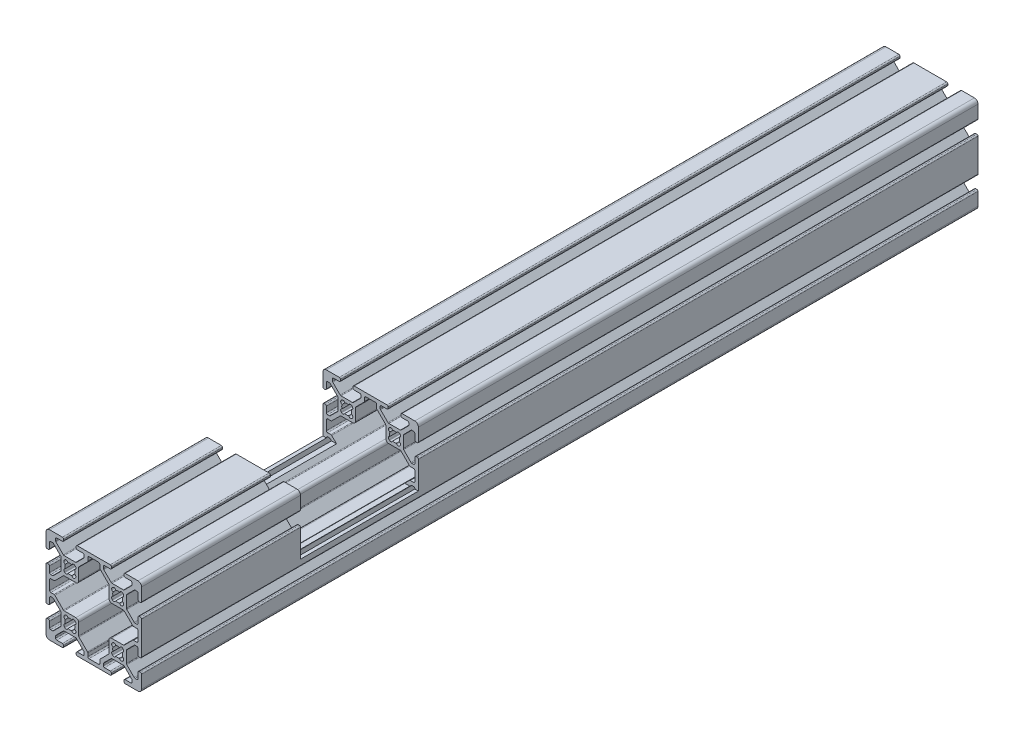
SolidWorks part; units mm, degrees
material "6105-T5 Aluminum"
ref_plane "Front Plane" through (0, 0, 0) normal (0, 0, 1) x (1, 0, 0)
ref_plane "Top Plane" through (0, 0, 0) normal (0, 1, 0) x (1, 0, 0)
ref_plane "Right Plane" through (0, 0, 0) normal (1, 0, 0) x (0, 0, -1)
sketch "Sketch1" plane through (0, 0, 0) normal (0, 0, 1) x (1, 0, 0)
  line L0 (-2.1249, 17.6955) -> (-2.3045, 17.8751)
  line L1 (-2.3045, 22.1249) -> (-2.1249, 22.3045)
  line L2 (2.1249, 22.3045) -> (2.3045, 22.1249)
  line L3 (2.3045, 17.8751) -> (2.1249, 17.6955)
  line L4 (-22.1249, 17.6955) -> (-22.3045, 17.8751)
  line L5 (-22.3045, 22.1249) -> (-22.1249, 22.3045)
  line L6 (-17.8751, 22.3045) -> (-17.6955, 22.1249)
  line L7 (-17.6955, 17.8751) -> (-17.8751, 17.6955)
  line L8 (-2.1249, -2.3045) -> (-2.3045, -2.1249)
  line L9 (-2.3045, 2.1249) -> (-2.1249, 2.3045)
  line L10 (2.1249, 2.3045) -> (2.3045, 2.1249)
  line L11 (2.3045, -2.1249) -> (2.1249, -2.3045)
  line L12 (-12.505, -7.992) -> (-12.505, -6.6448)
  line L13 (-12.6538, -6.2856) -> (-16.1962, -2.7431)
  line L14 (-16.345, -2.3839) -> (-16.345, 2.512)
  line L15 (-17.488, 3.655) -> (-22.3839, 3.655)
  line L16 (-22.7431, 3.8038) -> (-26.2856, 7.3462)
  line L17 (-26.6448, 7.495) -> (-27.992, 7.495)
  line L18 (-28.5, 8.003) -> (-28.5, 11.997)
  line L19 (-27.992, 12.505) -> (-26.6448, 12.505)
  line L20 (-26.2856, 12.6538) -> (-22.7431, 16.1962)
  line L21 (-22.3839, 16.345) -> (-17.488, 16.345)
  line L22 (-16.345, 17.488) -> (-16.345, 22.3839)
  line L23 (-16.1962, 22.7431) -> (-12.6538, 26.2856)
  line L24 (-12.505, 26.6448) -> (-12.505, 27.992)
  line L25 (-11.997, 28.5) -> (-8.003, 28.5)
  line L26 (-7.495, 27.992) -> (-7.495, 26.6448)
  line L27 (-7.3462, 26.2856) -> (-3.8038, 22.7431)
  line L28 (-3.655, 22.3839) -> (-3.655, 17.488)
  line L29 (-2.512, 16.345) -> (2.3839, 16.345)
  line L30 (2.7431, 16.1962) -> (6.2856, 12.6538)
  line L31 (6.6448, 12.505) -> (7.992, 12.505)
  line L32 (8.5, 11.997) -> (8.5, 8.003)
  line L33 (7.992, 7.495) -> (6.6448, 7.495)
  line L34 (6.2856, 7.3462) -> (2.7431, 3.8038)
  line L35 (2.3839, 3.655) -> (-2.512, 3.655)
  line L36 (-3.655, 2.512) -> (-3.655, -2.3839)
  line L37 (-3.8038, -2.7431) -> (-7.3462, -6.2856)
  line L38 (-7.495, -6.6448) -> (-7.495, -7.992)
  line L39 (-8.003, -8.5) -> (-11.997, -8.5)
  line L40 (-22.1249, -2.3045) -> (-22.3045, -2.1249)
  line L41 (-22.3045, 2.1249) -> (-22.1249, 2.3045)
  line L42 (-17.8751, 2.3045) -> (-17.6955, 2.1249)
  line L43 (-17.6955, -2.1249) -> (-17.8751, -2.3045)
  line L44 (-22.3839, -3.655) -> (-17.6161, -3.655)
  line L45 (-17.2569, -3.8038) -> (-14.1538, -6.9069)
  line L46 (-14.005, -7.2661) -> (-14.005, -7.992)
  line L47 (-14.513, -8.5) -> (-16.862, -8.5)
  line L48 (-17.37, -9.008) -> (-17.37, -9.492)
  line L49 (-16.862, -10) -> (-3.138, -10)
  line L50 (-2.63, -9.492) -> (-2.63, -9.008)
  line L51 (-3.138, -8.5) -> (-5.487, -8.5)
  line L52 (-5.995, -7.992) -> (-5.995, -7.2661)
  line L53 (-5.8462, -6.9069) -> (-2.7431, -3.8038)
  line L54 (-2.3839, -3.655) -> (2.3839, -3.655)
  line L55 (2.7431, -3.8038) -> (5.8462, -6.9069)
  line L56 (5.995, -7.2661) -> (5.995, -7.992)
  line L57 (5.487, -8.5) -> (3.138, -8.5)
  line L58 (2.63, -9.008) -> (2.63, -9.492)
  line L59 (3.138, -10) -> (8.5, -10)
  line L60 (10, -8.5) -> (10, -3.138)
  line L61 (9.492, -2.63) -> (9.008, -2.63)
  line L62 (8.5, -3.138) -> (8.5, -5.487)
  line L63 (7.992, -5.995) -> (7.2661, -5.995)
  line L64 (6.9069, -5.8462) -> (3.8038, -2.7431)
  line L65 (3.655, -2.3839) -> (3.655, 2.3839)
  line L66 (3.8038, 2.7431) -> (6.9069, 5.8462)
  line L67 (7.2661, 5.995) -> (7.992, 5.995)
  line L68 (8.5, 5.487) -> (8.5, 3.138)
  line L69 (9.008, 2.63) -> (9.492, 2.63)
  line L70 (10, 3.138) -> (10, 16.862)
  line L71 (9.492, 17.37) -> (9.008, 17.37)
  line L72 (8.5, 16.862) -> (8.5, 14.513)
  line L73 (7.992, 14.005) -> (7.2661, 14.005)
  line L74 (6.9069, 14.1538) -> (3.8038, 17.2569)
  line L75 (3.655, 17.6161) -> (3.655, 22.3839)
  line L76 (3.8038, 22.7431) -> (6.9069, 25.8462)
  line L77 (7.2661, 25.995) -> (7.992, 25.995)
  line L78 (8.5, 25.487) -> (8.5, 23.138)
  line L79 (9.008, 22.63) -> (9.492, 22.63)
  line L80 (10, 23.138) -> (10, 28.5)
  line L81 (8.5, 30) -> (3.138, 30)
  line L82 (2.63, 29.492) -> (2.63, 29.008)
  line L83 (3.138, 28.5) -> (5.487, 28.5)
  line L84 (5.995, 27.992) -> (5.995, 27.2661)
  line L85 (5.8462, 26.9069) -> (2.7431, 23.8038)
  line L86 (2.3839, 23.655) -> (-2.3839, 23.655)
  line L87 (-2.7431, 23.8038) -> (-5.8462, 26.9069)
  line L88 (-5.995, 27.2661) -> (-5.995, 27.992)
  line L89 (-5.487, 28.5) -> (-3.138, 28.5)
  line L90 (-2.63, 29.008) -> (-2.63, 29.492)
  line L91 (-3.138, 30) -> (-16.862, 30)
  line L92 (-17.37, 29.492) -> (-17.37, 29.008)
  line L93 (-16.862, 28.5) -> (-14.513, 28.5)
  line L94 (-14.005, 27.992) -> (-14.005, 27.2661)
  line L95 (-14.1538, 26.9069) -> (-17.2569, 23.8038)
  line L96 (-17.6161, 23.655) -> (-22.3839, 23.655)
  line L97 (-22.7431, 23.8038) -> (-25.8462, 26.9069)
  line L98 (-25.995, 27.2661) -> (-25.995, 27.992)
  line L99 (-25.487, 28.5) -> (-23.138, 28.5)
  line L100 (-22.63, 29.008) -> (-22.63, 29.492)
  line L101 (-23.138, 30) -> (-28.5, 30)
  line L102 (-30, 28.5) -> (-30, 23.138)
  line L103 (-29.492, 22.63) -> (-29.008, 22.63)
  line L104 (-28.5, 23.138) -> (-28.5, 25.487)
  line L105 (-27.992, 25.995) -> (-27.2661, 25.995)
  line L106 (-26.9069, 25.8462) -> (-23.8038, 22.7431)
  line L107 (-23.655, 22.3839) -> (-23.655, 17.6161)
  line L108 (-23.8038, 17.2569) -> (-26.9069, 14.1538)
  line L109 (-27.2661, 14.005) -> (-27.992, 14.005)
  line L110 (-28.5, 14.513) -> (-28.5, 16.862)
  line L111 (-29.008, 17.37) -> (-29.492, 17.37)
  line L112 (-30, 16.862) -> (-30, 3.138)
  line L113 (-29.492, 2.63) -> (-29.008, 2.63)
  line L114 (-28.5, 3.138) -> (-28.5, 5.487)
  line L115 (-27.992, 5.995) -> (-27.2661, 5.995)
  line L116 (-26.9069, 5.8462) -> (-23.8038, 2.7431)
  line L117 (-23.655, 2.3839) -> (-23.655, -2.3839)
  line L118 (-23.8038, -2.7431) -> (-26.9069, -5.8462)
  line L119 (-27.2661, -5.995) -> (-27.992, -5.995)
  line L120 (-28.5, -5.487) -> (-28.5, -3.138)
  line L121 (-29.008, -2.63) -> (-29.492, -2.63)
  line L122 (-30, -3.138) -> (-30, -8.5)
  line L123 (-28.5, -10) -> (-23.138, -10)
  line L124 (-22.63, -9.492) -> (-22.63, -9.008)
  line L125 (-23.138, -8.5) -> (-25.487, -8.5)
  line L126 (-25.995, -7.992) -> (-25.995, -7.2661)
  line L127 (-25.8462, -6.9069) -> (-22.7431, -3.8038)
  arc A0 (-1.9351, 19.196) -> (-2.3045, 17.8751) centre (-1.748, 18.4316) ccw
  arc A1 (-1.9351, 20.804) -> (-1.9351, 19.196) centre (0, 20) ccw
  arc A2 (-2.3045, 22.1249) -> (-1.9351, 20.804) centre (-1.748, 21.5684) ccw
  arc A3 (-0.804, 21.9351) -> (-2.1249, 22.3045) centre (-1.5684, 21.748) ccw
  arc A4 (0.804, 21.9351) -> (-0.804, 21.9351) centre (0, 20) ccw
  arc A5 (2.1249, 22.3045) -> (0.804, 21.9351) centre (1.5684, 21.748) ccw
  arc A6 (1.9351, 20.804) -> (2.3045, 22.1249) centre (1.748, 21.5684) ccw
  arc A7 (1.9351, 19.196) -> (1.9351, 20.804) centre (0, 20) ccw
  arc A8 (2.3045, 17.8751) -> (1.9351, 19.196) centre (1.748, 18.4316) ccw
  arc A9 (0.804, 18.0649) -> (2.1249, 17.6955) centre (1.5684, 18.252) ccw
  arc A10 (-0.804, 18.0649) -> (0.804, 18.0649) centre (0, 20) ccw
  arc A11 (-2.1249, 17.6955) -> (-0.804, 18.0649) centre (-1.5684, 18.252) ccw
  arc A12 (-21.9351, 19.196) -> (-22.3045, 17.8751) centre (-21.748, 18.4316) ccw
  arc A13 (-21.9351, 20.804) -> (-21.9351, 19.196) centre (-20, 20) ccw
  arc A14 (-22.3045, 22.1249) -> (-21.9351, 20.804) centre (-21.748, 21.5684) ccw
  arc A15 (-20.804, 21.9351) -> (-22.1249, 22.3045) centre (-21.5684, 21.748) ccw
  arc A16 (-19.196, 21.9351) -> (-20.804, 21.9351) centre (-20, 20) ccw
  arc A17 (-17.8751, 22.3045) -> (-19.196, 21.9351) centre (-18.4316, 21.748) ccw
  arc A18 (-18.0649, 20.804) -> (-17.6955, 22.1249) centre (-18.252, 21.5684) ccw
  arc A19 (-18.0649, 19.196) -> (-18.0649, 20.804) centre (-20, 20) ccw
  arc A20 (-17.6955, 17.8751) -> (-18.0649, 19.196) centre (-18.252, 18.4316) ccw
  arc A21 (-19.196, 18.0649) -> (-17.8751, 17.6955) centre (-18.4316, 18.252) ccw
  arc A22 (-20.804, 18.0649) -> (-19.196, 18.0649) centre (-20, 20) ccw
  arc A23 (-22.1249, 17.6955) -> (-20.804, 18.0649) centre (-21.5684, 18.252) ccw
  arc A24 (-1.9351, -0.804) -> (-2.3045, -2.1249) centre (-1.748, -1.5684) ccw
  arc A25 (-1.9351, 0.804) -> (-1.9351, -0.804) centre (0, 0) ccw
  arc A26 (-2.3045, 2.1249) -> (-1.9351, 0.804) centre (-1.748, 1.5684) ccw
  arc A27 (-0.804, 1.9351) -> (-2.1249, 2.3045) centre (-1.5684, 1.748) ccw
  arc A28 (0.804, 1.9351) -> (-0.804, 1.9351) centre (0, 0) ccw
  arc A29 (2.1249, 2.3045) -> (0.804, 1.9351) centre (1.5684, 1.748) ccw
  arc A30 (1.9351, 0.804) -> (2.3045, 2.1249) centre (1.748, 1.5684) ccw
  arc A31 (1.9351, -0.804) -> (1.9351, 0.804) centre (0, 0) ccw
  arc A32 (2.3045, -2.1249) -> (1.9351, -0.804) centre (1.748, -1.5684) ccw
  arc A33 (0.804, -1.9351) -> (2.1249, -2.3045) centre (1.5684, -1.748) ccw
  arc A34 (-0.804, -1.9351) -> (0.804, -1.9351) centre (0, 0) ccw
  arc A35 (-2.1249, -2.3045) -> (-0.804, -1.9351) centre (-1.5684, -1.748) ccw
  arc A36 (-12.505, -7.992) -> (-11.997, -8.5) centre (-11.997, -7.992) ccw
  arc A37 (-12.505, -6.6448) -> (-12.6538, -6.2856) centre (-13.013, -6.6448) ccw
  arc A38 (-16.345, -2.3839) -> (-16.1962, -2.7431) centre (-15.837, -2.3839) ccw
  arc A39 (-16.345, 2.512) -> (-17.488, 3.655) centre (-17.488, 2.512) ccw
  arc A40 (-22.7431, 3.8038) -> (-22.3839, 3.655) centre (-22.3839, 4.163) ccw
  arc A41 (-26.2856, 7.3462) -> (-26.6448, 7.495) centre (-26.6448, 6.987) ccw
  arc A42 (-28.5, 8.003) -> (-27.992, 7.495) centre (-27.992, 8.003) ccw
  arc A43 (-27.992, 12.505) -> (-28.5, 11.997) centre (-27.992, 11.997) ccw
  arc A44 (-26.6448, 12.505) -> (-26.2856, 12.6538) centre (-26.6448, 13.013) ccw
  arc A45 (-22.3839, 16.345) -> (-22.7431, 16.1962) centre (-22.3839, 15.837) ccw
  arc A46 (-17.488, 16.345) -> (-16.345, 17.488) centre (-17.488, 17.488) ccw
  arc A47 (-16.1962, 22.7431) -> (-16.345, 22.3839) centre (-15.837, 22.3839) ccw
  arc A48 (-12.6538, 26.2856) -> (-12.505, 26.6448) centre (-13.013, 26.6448) ccw
  arc A49 (-11.997, 28.5) -> (-12.505, 27.992) centre (-11.997, 27.992) ccw
  arc A50 (-7.495, 27.992) -> (-8.003, 28.5) centre (-8.003, 27.992) ccw
  arc A51 (-7.495, 26.6448) -> (-7.3462, 26.2856) centre (-6.987, 26.6448) ccw
  arc A52 (-3.655, 22.3839) -> (-3.8038, 22.7431) centre (-4.163, 22.3839) ccw
  arc A53 (-3.655, 17.488) -> (-2.512, 16.345) centre (-2.512, 17.488) ccw
  arc A54 (2.7431, 16.1962) -> (2.3839, 16.345) centre (2.3839, 15.837) ccw
  arc A55 (6.2856, 12.6538) -> (6.6448, 12.505) centre (6.6448, 13.013) ccw
  arc A56 (8.5, 11.997) -> (7.992, 12.505) centre (7.992, 11.997) ccw
  arc A57 (7.992, 7.495) -> (8.5, 8.003) centre (7.992, 8.003) ccw
  arc A58 (6.6448, 7.495) -> (6.2856, 7.3462) centre (6.6448, 6.987) ccw
  arc A59 (2.3839, 3.655) -> (2.7431, 3.8038) centre (2.3839, 4.163) ccw
  arc A60 (-2.512, 3.655) -> (-3.655, 2.512) centre (-2.512, 2.512) ccw
  arc A61 (-3.8038, -2.7431) -> (-3.655, -2.3839) centre (-4.163, -2.3839) ccw
  arc A62 (-7.3462, -6.2856) -> (-7.495, -6.6448) centre (-6.987, -6.6448) ccw
  arc A63 (-8.003, -8.5) -> (-7.495, -7.992) centre (-8.003, -7.992) ccw
  arc A64 (-21.9351, -0.804) -> (-22.3045, -2.1249) centre (-21.748, -1.5684) ccw
  arc A65 (-21.9351, 0.804) -> (-21.9351, -0.804) centre (-20, 0) ccw
  arc A66 (-22.3045, 2.1249) -> (-21.9351, 0.804) centre (-21.748, 1.5684) ccw
  arc A67 (-20.804, 1.9351) -> (-22.1249, 2.3045) centre (-21.5684, 1.748) ccw
  arc A68 (-19.196, 1.9351) -> (-20.804, 1.9351) centre (-20, 0) ccw
  arc A69 (-17.8751, 2.3045) -> (-19.196, 1.9351) centre (-18.4316, 1.748) ccw
  arc A70 (-18.0649, 0.804) -> (-17.6955, 2.1249) centre (-18.252, 1.5684) ccw
  arc A71 (-18.0649, -0.804) -> (-18.0649, 0.804) centre (-20, 0) ccw
  arc A72 (-17.6955, -2.1249) -> (-18.0649, -0.804) centre (-18.252, -1.5684) ccw
  arc A73 (-19.196, -1.9351) -> (-17.8751, -2.3045) centre (-18.4316, -1.748) ccw
  arc A74 (-20.804, -1.9351) -> (-19.196, -1.9351) centre (-20, 0) ccw
  arc A75 (-22.1249, -2.3045) -> (-20.804, -1.9351) centre (-21.5684, -1.748) ccw
  arc A76 (-22.3839, -3.655) -> (-22.7431, -3.8038) centre (-22.3839, -4.163) ccw
  arc A77 (-17.2569, -3.8038) -> (-17.6161, -3.655) centre (-17.6161, -4.163) ccw
  arc A78 (-14.005, -7.2661) -> (-14.1538, -6.9069) centre (-14.513, -7.2661) ccw
  arc A79 (-14.513, -8.5) -> (-14.005, -7.992) centre (-14.513, -7.992) ccw
  arc A80 (-16.862, -8.5) -> (-17.37, -9.008) centre (-16.862, -9.008) ccw
  arc A81 (-17.37, -9.492) -> (-16.862, -10) centre (-16.862, -9.492) ccw
  arc A82 (-3.138, -10) -> (-2.63, -9.492) centre (-3.138, -9.492) ccw
  arc A83 (-2.63, -9.008) -> (-3.138, -8.5) centre (-3.138, -9.008) ccw
  arc A84 (-5.995, -7.992) -> (-5.487, -8.5) centre (-5.487, -7.992) ccw
  arc A85 (-5.8462, -6.9069) -> (-5.995, -7.2661) centre (-5.487, -7.2661) ccw
  arc A86 (-2.3839, -3.655) -> (-2.7431, -3.8038) centre (-2.3839, -4.163) ccw
  arc A87 (2.7431, -3.8038) -> (2.3839, -3.655) centre (2.3839, -4.163) ccw
  arc A88 (5.995, -7.2661) -> (5.8462, -6.9069) centre (5.487, -7.2661) ccw
  arc A89 (5.487, -8.5) -> (5.995, -7.992) centre (5.487, -7.992) ccw
  arc A90 (3.138, -8.5) -> (2.63, -9.008) centre (3.138, -9.008) ccw
  arc A91 (2.63, -9.492) -> (3.138, -10) centre (3.138, -9.492) ccw
  arc A92 (8.5, -10) -> (10, -8.5) centre (8.5, -8.5) ccw
  arc A93 (10, -3.138) -> (9.492, -2.63) centre (9.492, -3.138) ccw
  arc A94 (9.008, -2.63) -> (8.5, -3.138) centre (9.008, -3.138) ccw
  arc A95 (7.992, -5.995) -> (8.5, -5.487) centre (7.992, -5.487) ccw
  arc A96 (6.9069, -5.8462) -> (7.2661, -5.995) centre (7.2661, -5.487) ccw
  arc A97 (3.655, -2.3839) -> (3.8038, -2.7431) centre (4.163, -2.3839) ccw
  arc A98 (3.8038, 2.7431) -> (3.655, 2.3839) centre (4.163, 2.3839) ccw
  arc A99 (7.2661, 5.995) -> (6.9069, 5.8462) centre (7.2661, 5.487) ccw
  arc A100 (8.5, 5.487) -> (7.992, 5.995) centre (7.992, 5.487) ccw
  arc A101 (8.5, 3.138) -> (9.008, 2.63) centre (9.008, 3.138) ccw
  arc A102 (9.492, 2.63) -> (10, 3.138) centre (9.492, 3.138) ccw
  arc A103 (10, 16.862) -> (9.492, 17.37) centre (9.492, 16.862) ccw
  arc A104 (9.008, 17.37) -> (8.5, 16.862) centre (9.008, 16.862) ccw
  arc A105 (7.992, 14.005) -> (8.5, 14.513) centre (7.992, 14.513) ccw
  arc A106 (6.9069, 14.1538) -> (7.2661, 14.005) centre (7.2661, 14.513) ccw
  arc A107 (3.655, 17.6161) -> (3.8038, 17.2569) centre (4.163, 17.6161) ccw
  arc A108 (3.8038, 22.7431) -> (3.655, 22.3839) centre (4.163, 22.3839) ccw
  arc A109 (7.2661, 25.995) -> (6.9069, 25.8462) centre (7.2661, 25.487) ccw
  arc A110 (8.5, 25.487) -> (7.992, 25.995) centre (7.992, 25.487) ccw
  arc A111 (8.5, 23.138) -> (9.008, 22.63) centre (9.008, 23.138) ccw
  arc A112 (9.492, 22.63) -> (10, 23.138) centre (9.492, 23.138) ccw
  arc A113 (10, 28.5) -> (8.5, 30) centre (8.5, 28.5) ccw
  arc A114 (3.138, 30) -> (2.63, 29.492) centre (3.138, 29.492) ccw
  arc A115 (2.63, 29.008) -> (3.138, 28.5) centre (3.138, 29.008) ccw
  arc A116 (5.995, 27.992) -> (5.487, 28.5) centre (5.487, 27.992) ccw
  arc A117 (5.8462, 26.9069) -> (5.995, 27.2661) centre (5.487, 27.2661) ccw
  arc A118 (2.3839, 23.655) -> (2.7431, 23.8038) centre (2.3839, 24.163) ccw
  arc A119 (-2.7431, 23.8038) -> (-2.3839, 23.655) centre (-2.3839, 24.163) ccw
  arc A120 (-5.995, 27.2661) -> (-5.8462, 26.9069) centre (-5.487, 27.2661) ccw
  arc A121 (-5.487, 28.5) -> (-5.995, 27.992) centre (-5.487, 27.992) ccw
  arc A122 (-3.138, 28.5) -> (-2.63, 29.008) centre (-3.138, 29.008) ccw
  arc A123 (-2.63, 29.492) -> (-3.138, 30) centre (-3.138, 29.492) ccw
  arc A124 (-16.862, 30) -> (-17.37, 29.492) centre (-16.862, 29.492) ccw
  arc A125 (-17.37, 29.008) -> (-16.862, 28.5) centre (-16.862, 29.008) ccw
  arc A126 (-14.005, 27.992) -> (-14.513, 28.5) centre (-14.513, 27.992) ccw
  arc A127 (-14.1538, 26.9069) -> (-14.005, 27.2661) centre (-14.513, 27.2661) ccw
  arc A128 (-17.6161, 23.655) -> (-17.2569, 23.8038) centre (-17.6161, 24.163) ccw
  arc A129 (-22.7431, 23.8038) -> (-22.3839, 23.655) centre (-22.3839, 24.163) ccw
  arc A130 (-25.995, 27.2661) -> (-25.8462, 26.9069) centre (-25.487, 27.2661) ccw
  arc A131 (-25.487, 28.5) -> (-25.995, 27.992) centre (-25.487, 27.992) ccw
  arc A132 (-23.138, 28.5) -> (-22.63, 29.008) centre (-23.138, 29.008) ccw
  arc A133 (-22.63, 29.492) -> (-23.138, 30) centre (-23.138, 29.492) ccw
  arc A134 (-28.5, 30) -> (-30, 28.5) centre (-28.5, 28.5) ccw
  arc A135 (-30, 23.138) -> (-29.492, 22.63) centre (-29.492, 23.138) ccw
  arc A136 (-29.008, 22.63) -> (-28.5, 23.138) centre (-29.008, 23.138) ccw
  arc A137 (-27.992, 25.995) -> (-28.5, 25.487) centre (-27.992, 25.487) ccw
  arc A138 (-26.9069, 25.8462) -> (-27.2661, 25.995) centre (-27.2661, 25.487) ccw
  arc A139 (-23.655, 22.3839) -> (-23.8038, 22.7431) centre (-24.163, 22.3839) ccw
  arc A140 (-23.8038, 17.2569) -> (-23.655, 17.6161) centre (-24.163, 17.6161) ccw
  arc A141 (-27.2661, 14.005) -> (-26.9069, 14.1538) centre (-27.2661, 14.513) ccw
  arc A142 (-28.5, 14.513) -> (-27.992, 14.005) centre (-27.992, 14.513) ccw
  arc A143 (-28.5, 16.862) -> (-29.008, 17.37) centre (-29.008, 16.862) ccw
  arc A144 (-29.492, 17.37) -> (-30, 16.862) centre (-29.492, 16.862) ccw
  arc A145 (-30, 3.138) -> (-29.492, 2.63) centre (-29.492, 3.138) ccw
  arc A146 (-29.008, 2.63) -> (-28.5, 3.138) centre (-29.008, 3.138) ccw
  arc A147 (-27.992, 5.995) -> (-28.5, 5.487) centre (-27.992, 5.487) ccw
  arc A148 (-26.9069, 5.8462) -> (-27.2661, 5.995) centre (-27.2661, 5.487) ccw
  arc A149 (-23.655, 2.3839) -> (-23.8038, 2.7431) centre (-24.163, 2.3839) ccw
  arc A150 (-23.8038, -2.7431) -> (-23.655, -2.3839) centre (-24.163, -2.3839) ccw
  arc A151 (-27.2661, -5.995) -> (-26.9069, -5.8462) centre (-27.2661, -5.487) ccw
  arc A152 (-28.5, -5.487) -> (-27.992, -5.995) centre (-27.992, -5.487) ccw
  arc A153 (-28.5, -3.138) -> (-29.008, -2.63) centre (-29.008, -3.138) ccw
  arc A154 (-29.492, -2.63) -> (-30, -3.138) centre (-29.492, -3.138) ccw
  arc A155 (-30, -8.5) -> (-28.5, -10) centre (-28.5, -8.5) ccw
  arc A156 (-23.138, -10) -> (-22.63, -9.492) centre (-23.138, -9.492) ccw
  arc A157 (-22.63, -9.008) -> (-23.138, -8.5) centre (-23.138, -9.008) ccw
  arc A158 (-25.995, -7.992) -> (-25.487, -8.5) centre (-25.487, -7.992) ccw
  arc A159 (-25.8462, -6.9069) -> (-25.995, -7.2661) centre (-25.487, -7.2661) ccw
extrude "Extrude1" add sketch "Sketch1" against normal blind 350
sketch "Sketch2" plane through (10, 0, 0) normal (1, 0, 0) x (0, 0, -1)
  line L1 (66.4865, 5.3292) -> (115.8417, 5.3292)
  line L2 (66.4865, 5.3292) -> (66.4865, 33.8339)
  line L3 (66.4865, 33.8339) -> (115.8417, 33.8339)
  line L4 (115.8417, 5.3292) -> (115.8417, 33.8339)
  point P4 (123.9925, 1.0555)
  point P5 (59.8115, 34.7782)
  point P6 (59.1176, 33.8339)
  point P7 (58.7336, 4.7584)
  point P8 (60.7374, 5.3292)
extrude "Cut-Extrude1" cut sketch "Sketch2" against normal blind 54 contours L2 L3 L4 L1
